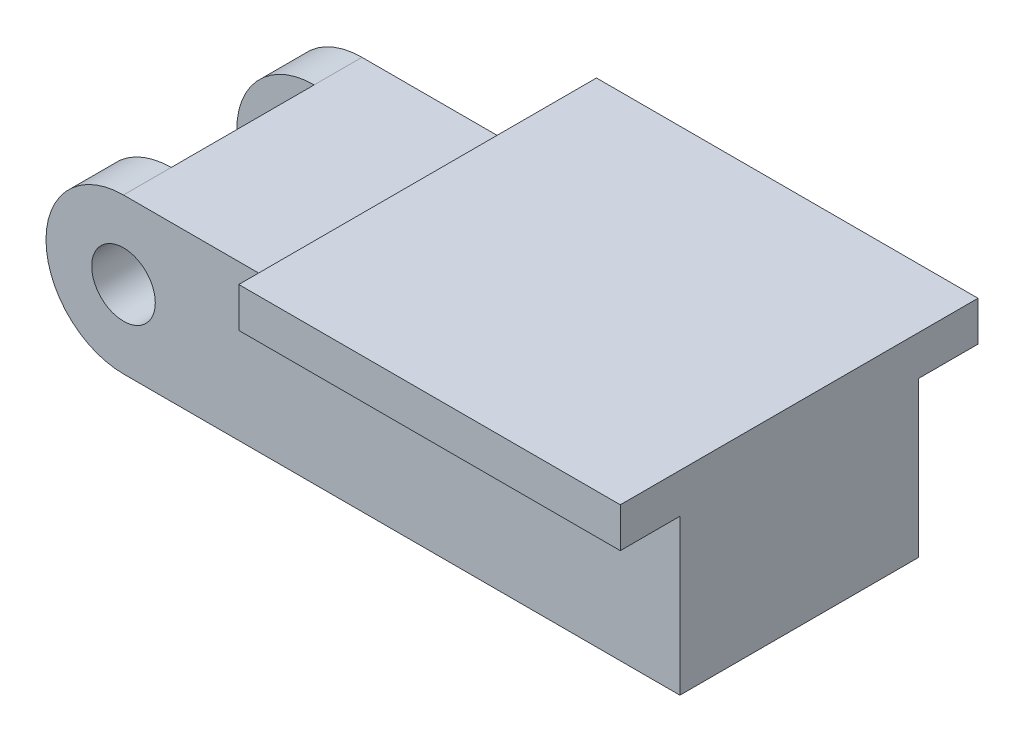
SolidWorks part; units mm, degrees
ref_plane "Front Plane" through (0, 0, 0) normal (0, 0, 1) x (1, 0, 0)
ref_plane "Top Plane" through (0, 0, 0) normal (0, 1, 0) x (1, 0, 0)
ref_plane "Right Plane" through (0, 0, 0) normal (1, 0, 0) x (0, 0, -1)
sketch "Sketch1" plane through (0, 0, 0) normal (1, 0, 0) x (0, 0, -1)
  line L1 (-15, 0) -> (15, 0)
  line L2 (-15, 0) -> (-15, 19.5)
  line L3 (-15, 19.5) -> (15, 19.5)
  line L4 (15, 0) -> (15, 19.5)
  point P4 (0, 0)
  dimension "D1" = 30
  dimension "D2" = 19.5
extrude "Boss-Extrude1" add sketch "Sketch1" against normal blind 70
sketch "Sketch6" plane through (0, 0, 15) normal (0, 0, 1) x (1, 0, 0)
  line L0 (-70, 19.5) -> (-70, 0) construction
  line L1 (-70, 19.5) -> (-70, 0)
  arc A0 (-70, 19.5) -> (-70, 0) centre (-70, 9.75) ccw
extrude "Boss-Extrude2" add sketch "Sketch6" against normal up to surface (30 mm away) up to face at (-35, 9.75, -15)
sketch "Sketch7" plane through (0, 19.5, 0) normal (0, 1, 0) x (1, 0, 0)
  line L1 (-48, 22.5) -> (0, 22.5)
  line L2 (-48, 22.5) -> (-48, -22.5)
  line L3 (-48, -22.5) -> (0, -22.5)
  line L4 (0, 22.5) -> (0, -22.5)
  point P4 (0, 0)
  dimension "D1" = 48
  dimension "D2" = 45
extrude "Boss-Extrude3" add sketch "Sketch7" along normal blind 5
sketch "Sketch8" plane through (0, 0, 15) normal (0, 0, 1) x (1, 0, 0)
  line L0 (-70, 19.5) -> (-70, 0) construction
  circle A0 centre (-70, 9.75) radius 9.75
extrude "Cut-Extrude2" cut sketch "Sketch8" against normal offset from surface (18 mm away) 6 from offset 6 up to face at (-39.55, 11.7, -15) offset against normal yes
sketch "Sketch9" plane through (0, 0, 15) normal (0, 0, 1) x (1, 0, 0)
  line L0 (-70, 19.5) -> (-70, 0) construction
  circle A0 centre (-70, 9.75) radius 4
  dimension "D1" = 8
extrude "Cut-Extrude3" cut sketch "Sketch9" against normal through all
sketch "Sketch10" plane through (0, 0, 0) normal (0, -1, 0) x (1, 0, 0)
  line L0 (0, 0) -> (-49.6118, 0) construction
  line L2 (-48, 22.5) -> (0, 22.5) construction
  line L3 (-24, 22.5) -> (-24, -11.6735) construction
  circle A0 centre (-24, 0) radius 9
  dimension "D1" = 18
extrude "Cut-Extrude4" cut sketch "Sketch10" against normal blind 10
sketch "Sketch11" plane through (0, 0, -15) normal (0, 0, -1) x (-1, 0, 0)
  line L0 (66.5615, 11.7937) -> (45, 0)
  line L1 (70, 0) -> (0, 0) construction
  line L2 (45, 0) -> (70, 0)
  line L3 (70, 0) -> (66.5615, 11.7937)
  circle A0 centre (70, 9.75) radius 4 construction
  point P6 (0, 0)
  point P9 (0, 0)
  point P10 (66.5615, 11.7937)
  dimension "D1" = 25
  dimension "D2" = 24.5762
extrude "Cut-Extrude6" cut sketch "Sketch11" against normal blind 18 from offset 6 offset against normal yes
fillet "Fillet1" radius 10 1 edges at (-60.3448, 8.3933, 0)
